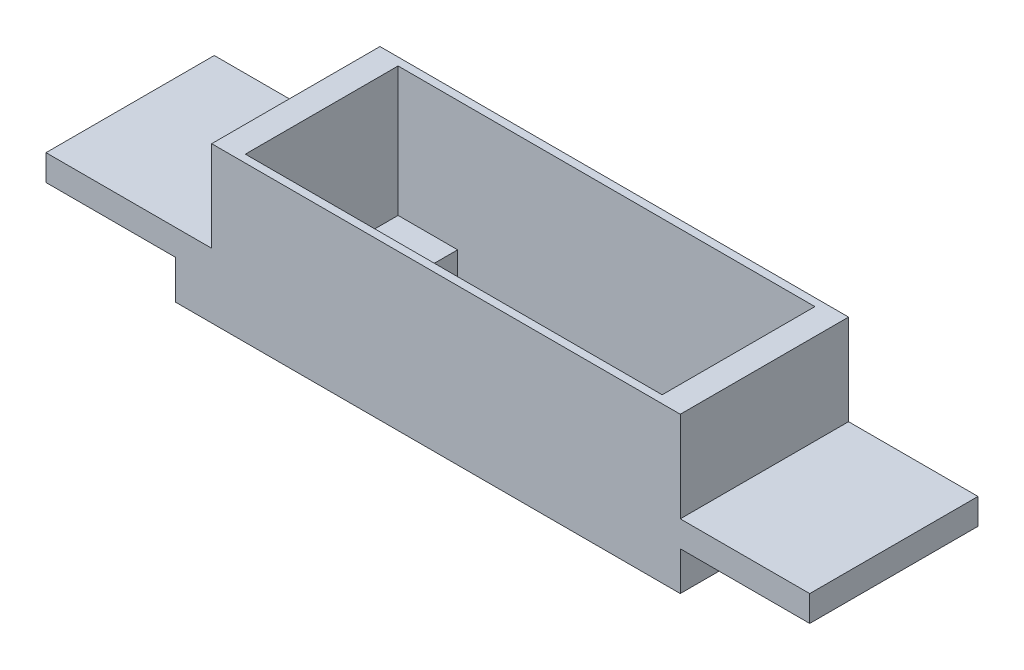
SolidWorks part; units mm, degrees
ref_plane "Front Plane" through (0, 0, 0) normal (0, 0, 1) x (1, 0, 0)
ref_plane "Top Plane" through (0, 0, 0) normal (0, 1, 0) x (1, 0, 0)
ref_plane "Right Plane" through (0, 0, 0) normal (1, 0, 0) x (0, 0, -1)
sketch "Sketch1" plane through (0, 0, 0) normal (0, 1, 0) x (1, 0, 0)
  line L1 (-19.5, 6.5) -> (19.5, 6.5)
  line L2 (-19.5, 6.5) -> (-19.5, -6.5)
  line L3 (-19.5, -6.5) -> (19.5, -6.5)
  line L4 (19.5, 6.5) -> (19.5, -6.5)
  line L5 (-19.5, 6.5) -> (19.5, -6.5) construction
  line L6 (-19.5, -6.5) -> (19.5, 6.5) construction
  point P0 (0, 0)
  dimension "D1" = 39
  dimension "D2" = 13
extrude "Boss-Extrude1" add sketch "Sketch1" along normal blind 2
sketch "Sketch3" plane through (0, 2, 0) normal (0, 1, 0) x (1, 0, 0)
  line L0 (-19.5, -6.5) -> (19.5, -6.5) construction
  line L1 (19.5, 6.5) -> (17.5, 6.5)
  line L2 (19.5, 6.5) -> (19.5, -6.5)
  line L3 (19.5, -6.5) -> (17.5, -6.5)
  line L4 (17.5, 6.5) -> (17.5, -6.5)
  line L6 (-19.5, 6.5) -> (-14.7, 6.5)
  line L7 (-19.5, 6.5) -> (-19.5, -6.5)
  line L8 (-19.5, -6.5) -> (-14.7, -6.5)
  line L9 (-14.7, 6.5) -> (-14.7, -6.5)
  dimension "D1" = 2
  dimension "D2" = 32.2
extrude "Boss-Extrude2" add sketch "Sketch3" along normal blind 1
sketch "Sketch4" plane through (0, 3, 0) normal (0, 1, 0) x (1, 0, 0)
  line L0 (19.5, -6.5) -> (19.5, 6.5) construction
  line L1 (-14.7, 6.5) -> (-29.5, 6.5)
  line L2 (-14.7, 6.5) -> (-14.7, -6.5)
  line L3 (-14.7, -6.5) -> (-29.5, -6.5)
  line L4 (-29.5, 6.5) -> (-29.5, -6.5)
  line L5 (17.5, 6.5) -> (29.5, 6.5)
  line L6 (17.5, 6.5) -> (17.5, -6.5)
  line L7 (17.5, -6.5) -> (29.5, -6.5)
  line L8 (29.5, 6.5) -> (29.5, -6.5)
  line L9 (-19.5, 6.5) -> (-19.5, -6.5) construction
  dimension "D1" = 13
  dimension "D2" = 13
  dimension "D3" = 10
  dimension "D4" = 10
extrude "Boss-Extrude3" add sketch "Sketch4" along normal blind 2
sketch "Sketch5" plane through (0, 2, 0) normal (0, 1, 0) x (1, 0, 0)
  line L0 (-14.7, 6.5) -> (17.5, -6.5) construction
  line L9 (17.5, 6.5) -> (-14.7, -6.5) construction
  line L11 (-10.1, 5.9) -> (12.9, 5.9)
  line L12 (-10.1, 5.9) -> (-10.1, -5.9)
  line L13 (-10.1, -5.9) -> (12.9, -5.9)
  line L14 (12.9, 5.9) -> (12.9, -5.9)
  line L15 (-10.1, 5.9) -> (12.9, -5.9) construction
  line L16 (-10.1, -5.9) -> (12.9, 5.9) construction
  point P0 (1.4, 0)
  dimension "D1" = 11.8
  dimension "D2" = 23
extrude "Cut-Extrude1" cut sketch "Sketch5" against normal through all
sketch "Sketch6" plane through (0, 2, 0) normal (0, 1, 0) x (1, 0, 0)
  line L0 (17.5, 0) -> (-14.7, 0) construction
  line L1 (17.5, 6.5) -> (17.5, -6.5) construction
  line L2 (-14.7, -6.5) -> (-14.7, 6.5) construction
  line L3 (-14.7, 6.5) -> (-10.1, -6.5) construction
  line L4 (-14.7, -6.5) -> (17.5, -6.5) construction
  line L5 (-14.7, -6.5) -> (-10.1, 6.5) construction
  line L6 (17.5, 6.5) -> (-14.7, 6.5) construction
  line L7 (12.9, 6.5) -> (17.5, -6.5) construction
  line L8 (17.5, 6.5) -> (12.9, -6.5) construction
  circle A0 centre (-12.4, 0) radius 1
  circle A1 centre (15.2, 0) radius 1
  dimension "D1" = 2
  dimension "D2" = 2
extrude "Boss-Extrude4" add sketch "Sketch6" along normal blind 3
sketch "Sketch7" plane through (0, 2, 0) normal (0, 1, 0) x (1, 0, 0)
  line L0 (17.5, 6.5) -> (17.5, -6.5) construction
  line L1 (-14.7, -6.5) -> (17.5, -6.5)
  line L2 (-14.7, -6.5) -> (-14.7, -5.9)
  line L3 (-14.7, -5.9) -> (17.5, -5.9)
  line L4 (17.5, -6.5) -> (17.5, -5.9)
  line L5 (12.9, 5.9) -> (-10.1, 5.9) construction
  line L6 (-14.7, 6.5) -> (17.5, 6.5)
  line L7 (-14.7, 6.5) -> (-14.7, 5.9)
  line L8 (-14.7, 5.9) -> (17.5, 5.9)
  line L9 (17.5, 6.5) -> (17.5, 5.9)
extrude "Boss-Extrude5" add sketch "Sketch7" along normal blind 10
sketch "Sketch8" plane through (0, 5, 0) normal (0, 1, 0) x (1, 0, 0)
  line L0 (-29.5, -6.5) -> (-14.7, -6.5) construction
  line L1 (-14.7, 6.5) -> (-16.7, 6.5)
  line L2 (-14.7, 6.5) -> (-14.7, -6.5)
  line L3 (-14.7, -6.5) -> (-16.7, -6.5)
  line L4 (-16.7, 6.5) -> (-16.7, -6.5)
  line L5 (17.5, -6.5) -> (29.5, -6.5) construction
  line L6 (17.5, 6.5) -> (19.5, 6.5)
  line L7 (17.5, 6.5) -> (17.5, -6.5)
  line L8 (17.5, -6.5) -> (19.5, -6.5)
  line L9 (19.5, 6.5) -> (19.5, -6.5)
  dimension "D1" = 2
  dimension "D2" = 2
extrude "Boss-Extrude6" add sketch "Sketch8" along normal up to surface (7 mm away) up to face at (1.4, 12, 6.2)
